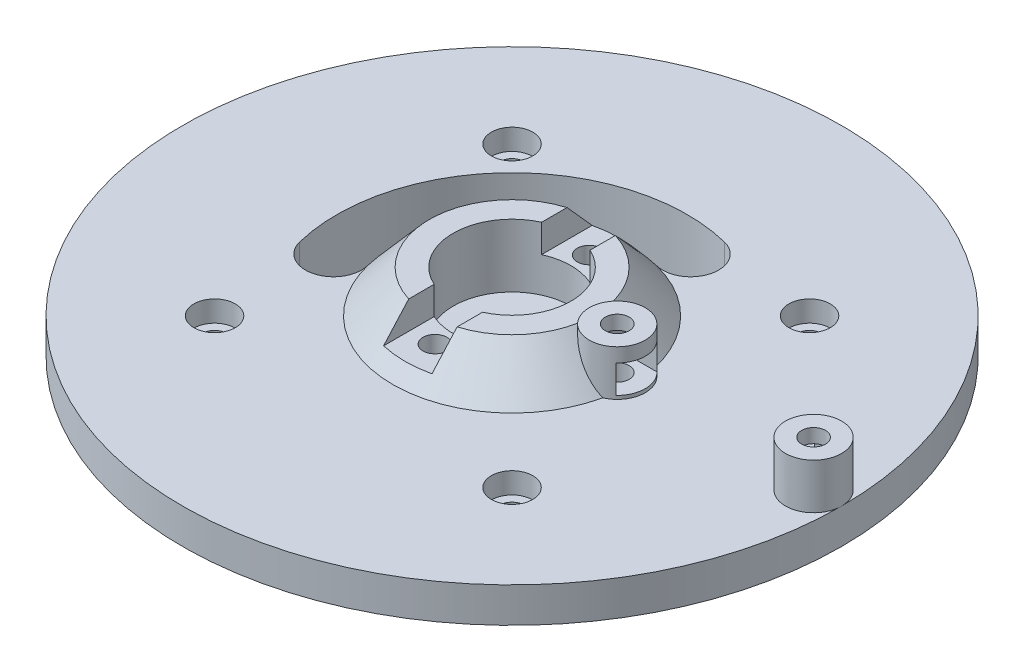
SolidWorks part; units mm, degrees
ref_plane "Front Plane" through (0, 0, 0) normal (0, 0, 1) x (1, 0, 0)
ref_plane "Top Plane" through (0, 0, 0) normal (0, 1, 0) x (1, 0, 0)
ref_plane "Right Plane" through (0, 0, 0) normal (1, 0, 0) x (0, 0, -1)
sketch "Sketch1" plane through (0, 0, 0) normal (0, 0, 1) x (1, 0, 0)
  line L0 (0, -62.2558) -> (0, 62.2558) construction
  line L1 (25, 0) -> (47, 0)
  line L2 (47, 0) -> (47, -5)
  line L3 (47, -5) -> (35, -5)
  line L4 (35, -5) -> (35, -11)
  line L5 (35, -11) -> (25, -11)
  line L6 (25, -11) -> (25, 0)
  point P3 (0, 0)
  dimension "D1" = 25
  dimension "D2" = 35
  dimension "D3" = 47
  dimension "D4" = 6
  dimension "D5" = 5
revolve "Revolve1" add sketch "Sketch1" angle 360 about L0
sketch "Sketch3" plane through (0, 0, 0) normal (0, 1, 0) x (1, 0, 0)
  line L1 (0, 30) -> (0, 0) construction
  line L2 (0, 0) -> (21.2132, 21.2132)
  circle A1 centre (21.2132, 21.2132) radius 1.7
  dimension "D1" = 3.4
  dimension "D2" = 30
  dimension "D3" = 30
  dimension "D4" = 45
extrude "Cut-Extrude1" cut sketch "Sketch3" against normal through all and the other way through all
pattern_circular "CirPattern1" count 4 over 360 about axis through (0, 0, 0) along (0, 1, 0) of "Cut-Extrude1"
sketch "Sketch4" plane through (0, 0, 0) normal (0, 1, 0) x (1, 0, 0)
  line L0 (-25, 0) -> (-17, 0) construction
  line L1 (0, 0) -> (-22.6577, -10.5655)
  line L2 (-17, 0) -> (-25, 0) construction
  line L3 (0, 0) -> (10.5655, 22.6577)
  line L4 (0, 0) -> (-17.6777, 17.6777)
  line L5 (0, 0) -> (25, 0) construction
  circle A0 centre (0, 0) radius 17
  circle A1 centre (0, 0) radius 25
  circle A2 centre (0, 0) radius 21 construction
  circle A3 centre (5.0873, 20.3745) radius 4
  circle A4 centre (-20.3745, -5.0873) radius 4
  circle M10 centre (0, 0) radius 25
  dimension "D1" = 34
  dimension "D5" = 8
  dimension "D6" = 4
  dimension "D7" = 8
  dimension "D8" = 8
  dimension "D2" = 135
  dimension "D3" = 70
  dimension "D4" = 70
extrude "Boss-Extrude1" add sketch "Sketch4" against normal through all contours L1 A0 L3 | L3 A0 L1 | A0 L1 L3 M10 | A4 L1 A0 | A4 L1 M10 | A3 A0 L3 | A3 L3 A1 | L3 A0 L4
sketch "Sketch5" plane through (0, 0, 0) normal (1, 0, 0) x (0, 0, -1)
  line L0 (0, 0) -> (0, -15.0602) construction
  line L1 (0, 0) -> (0, 11.1802) construction
  line L2 (-8.4, 0) -> (-8.4, 6)
  line L3 (47, 0) -> (-47, 0) construction
  line L4 (-8.4, 6) -> (-11.8, 6)
  line L5 (-11.8, 6) -> (-17, 0)
  line L7 (-17, 0) -> (-8.4, 0)
  dimension "D1" = 3.4
  dimension "D2" = 17
  dimension "D3" = 17
  dimension "D4" = 8.4
  dimension "D5" = 6
revolve "Revolve2" add sketch "Sketch5" angle 360 about L0
sketch "Sketch6" plane through (0, 0, 0) normal (0, 1, 0) x (1, 0, 0)
  circle A0 centre (0, 0) radius 8.4
extrude "Cut-Extrude2" cut sketch "Sketch6" against normal blind 3
sketch "Sketch7" plane through (0, 6, 0) normal (0, 1, 0) x (1, 0, 0)
  line L1 (-3.45, -20) -> (3.45, -20)
  line L2 (-3.45, -20) -> (-3.45, 20)
  line L3 (-3.45, 20) -> (3.45, 20)
  line L4 (3.45, -20) -> (3.45, 20)
  line L5 (-3.45, -20) -> (3.45, 20) construction
  line L6 (-3.45, 20) -> (3.45, -20) construction
  point P0 (0, 0)
  dimension "D1" = 6.9
  dimension "D2" = 40
extrude "Cut-Extrude3" cut sketch "Sketch7" against normal blind 4
sketch "Sketch8" plane through (0, 2, 0) normal (0, 1, 0) x (1, 0, 0)
  line L0 (0, 0) -> (0, -8.4) construction
  arc A2 (-3.45, -7.6588) -> (3.45, -7.6588) centre (0, 0) ccw construction
  circle A3 centre (0, 11) radius 1.7
  circle A4 centre (0, -11) radius 1.7
  dimension "D1" = 3.4
  dimension "D2" = 3.4
  dimension "D3" = 11
  dimension "D4" = 11
extrude "Cut-Extrude4" cut sketch "Sketch8" against normal through all
sketch "Sketch9" plane through (0, 0, 0) normal (0, 1, 0) x (1, 0, 0)
  circle A0 centre (43, 0) radius 4
  circle A1 centre (0, 0) radius 47 construction
  circle A2 centre (15, 0) radius 4
  dimension "D1" = 8
  dimension "D2" = 43
  dimension "D4" = 8
  dimension "D3" = 28
extrude "Boss-Extrude2" add sketch "Sketch9" along normal blind 6.5
sketch "Sketch10" plane through (0, 6.5, 0) normal (0, 1, 0) x (1, 0, 0)
  circle A0 centre (15, 0) radius 1.7
  circle A1 centre (43, 0) radius 1.7
  dimension "D1" = 3.4
  dimension "D2" = 3.4
extrude "Cut-Extrude5" cut sketch "Sketch10" against normal through all
ref_plane "Plane1" through (0, 3.5, 0) normal (0, 1, 0) x (1, 0, 0)
sketch "Sketch11" plane through (0, 3.5, 0) normal (0, 1, 0) x (1, 0, 0)
  line L0 (11.65, 0) -> (18.35, 0) construction
  line L1 (13.325, 2.9012) -> (16.675, -2.9012) construction
  line L2 (13.325, -2.9012) -> (16.675, 2.9012) construction
  line L3 (29, -6.1591) -> (29, 7.342) construction
  line L4 (13.325, 2.9012) -> (11.65, 0)
  line L5 (11.65, 0) -> (13.325, -2.9012)
  line L6 (13.325, -2.9012) -> (16.675, -2.9012)
  line L7 (16.675, -2.9012) -> (18.35, 0)
  line L8 (18.35, 0) -> (16.675, 2.9012)
  line L9 (16.675, 2.9012) -> (13.325, 2.9012)
  line L10 (39.65, 0) -> (41.325, 2.9012)
  line L11 (41.325, -2.9012) -> (39.65, 0)
  line L12 (44.675, -2.9012) -> (41.325, -2.9012)
  line L13 (46.35, 0) -> (44.675, -2.9012)
  line L14 (44.675, 2.9012) -> (46.35, 0)
  line L15 (41.325, 2.9012) -> (44.675, 2.9012)
  line L16 (16.675, 2.9012) -> (41.325, 2.9012)
  line L17 (16.675, -2.9012) -> (41.325, -2.9012)
  circle A0 centre (15, 0) radius 3.35 construction
  circle A1 centre (43, 0) radius 3.35 construction
  dimension "D1" = 6.7
  dimension "D5" = 6.7
  dimension "D2" = 60
  dimension "D3" = 60
  dimension "D4" = 14
extrude "Cut-Extrude6" cut sketch "Sketch11" against normal blind 3 and the other way blind 1 contours L8 L9 L4 L5 L6 L7 | L15 L10 L11 L12 L13 L14 | L7 L17 L11 L10 L16 L8
sketch "Sketch12" plane through (0, 0, 0) normal (0, 1, 0) x (1, 0, 0)
  circle A0 centre (-21.2132, 21.2132) radius 2.95
  dimension "D1" = 5.9
extrude "Cut-Extrude7" cut sketch "Sketch12" against normal blind 3
pattern_circular "CirPattern2" count 4 over 360 about axis through (0, 0, 0) along (0, 1, 0) of "Cut-Extrude7"
sketch "Sketch13" plane through (0, 0, 0) normal (0, 1, 0) x (1, 0, 0)
  line L0 (0, 0) -> (-21.2132, 21.2132) construction
  line L1 (0, 0) -> (43, 0) construction
  dimension "D1" = 135
sketch "Sketch14" plane through (0, -11, 0) normal (0, -1, 0) x (1, 0, 0)
  line L0 (-3.35, 11) -> (3.35, 11) construction
  line L1 (-1.675, 13.9012) -> (1.675, 8.0988) construction
  line L2 (-1.675, 8.0988) -> (1.675, 13.9012) construction
  line L3 (-1.675, 13.9012) -> (1.675, 13.9012)
  line L4 (1.675, 13.9012) -> (3.35, 11)
  line L5 (3.35, 11) -> (1.675, 8.0988)
  line L6 (1.675, 8.0988) -> (-1.675, 8.0988)
  line L7 (-1.675, 8.0988) -> (-3.35, 11)
  line L8 (-3.35, 11) -> (-1.675, 13.9012)
  line L9 (-8.2529, 0) -> (10.0552, 0) construction
  line L10 (-1.675, -8.0988) -> (-3.35, -11)
  line L11 (1.675, -8.0988) -> (-1.675, -8.0988)
  line L12 (3.35, -11) -> (1.675, -8.0988)
  line L13 (1.675, -13.9012) -> (3.35, -11)
  line L14 (-1.675, -13.9012) -> (1.675, -13.9012)
  line L15 (-3.35, -11) -> (-1.675, -13.9012)
  circle A0 centre (0, 11) radius 3.35 construction
  dimension "D1" = 6.7
  dimension "D2" = 60
  dimension "D3" = 60
extrude "Cut-Extrude8" cut sketch "Sketch14" against normal blind 3
